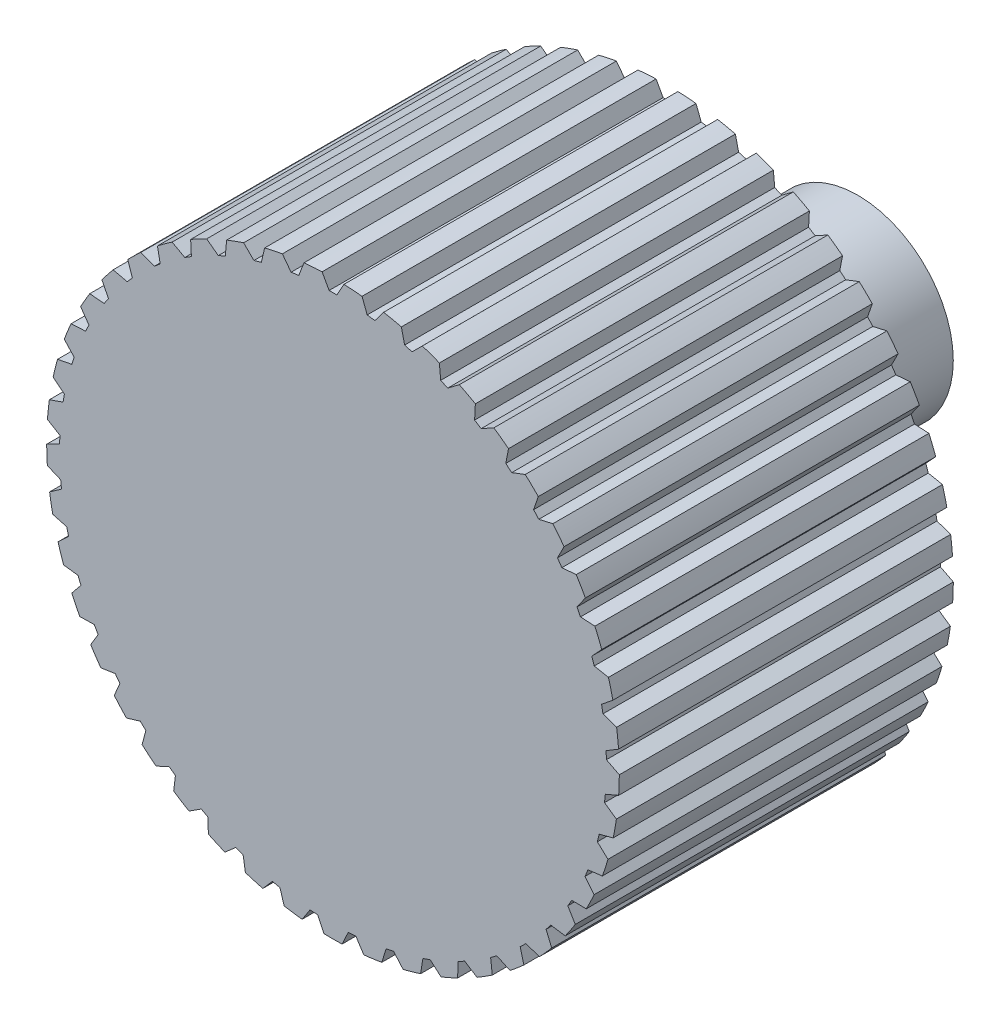
SolidWorks part; units mm, degrees
ref_plane "Plan de face" through (0, 0, 0) normal (0, 0, 1) x (1, 0, 0)
ref_plane "Plan de dessus" through (0, 0, 0) normal (0, 1, 0) x (1, 0, 0)
ref_plane "Plan de droite" through (0, 0, 0) normal (1, 0, 0) x (0, 0, -1)
sketch "Esquisse1" plane through (0, 0, 0) normal (0, 0, 1) x (1, 0, 0)
  line L0 (-0.1143, 2.9978) -> (-0.0406, 2.8652)
  line L1 (0.0406, 2.8652) -> (0.1143, 2.9978)
  line L2 (0, 2.8652) -> (0, 0) construction
  line L3 (-0.0406, 2.8652) -> (0.0406, 2.8652)
  line L4 (0.439, 2.8316) -> (0.5304, 2.9527)
  line L5 (0.3041, 2.9846) -> (0.3585, 2.8429)
  line L6 (0.3585, 2.8429) -> (0.439, 2.8316)
  line L7 (0.8288, 2.743) -> (0.9362, 2.8502)
  line L8 (0.7165, 2.9132) -> (0.7507, 2.7654)
  line L9 (0.7507, 2.7654) -> (0.8288, 2.743)
  line L10 (1.2025, 2.6009) -> (1.3237, 2.6922)
  line L11 (1.1149, 2.7851) -> (1.1283, 2.634)
  line L12 (1.1283, 2.634) -> (1.2025, 2.6009)
  line L13 (1.5527, 2.4083) -> (1.6855, 2.4817)
  line L14 (1.4917, 2.6029) -> (1.4839, 2.4513)
  line L15 (1.4839, 2.4513) -> (1.5527, 2.4083)
  line L16 (1.8728, 2.1687) -> (2.0145, 2.223)
  line L17 (1.8394, 2.3699) -> (1.8106, 2.2209)
  line L18 (1.8106, 2.2209) -> (1.8728, 2.1687)
  line L19 (2.1564, 1.887) -> (2.3043, 1.921)
  line L20 (2.1514, 2.0909) -> (2.1021, 1.9473)
  line L21 (2.1021, 1.9473) -> (2.1564, 1.887)
  line L22 (2.398, 1.5685) -> (2.5492, 1.5816)
  line L23 (2.4214, 1.7711) -> (2.3526, 1.6358)
  line L24 (2.3526, 1.6358) -> (2.398, 1.5685)
  line L25 (2.593, 1.2195) -> (2.7445, 1.2114)
  line L26 (2.6443, 1.4169) -> (2.5574, 1.2925)
  line L27 (2.5574, 1.2925) -> (2.593, 1.2195)
  line L28 (2.7375, 0.8468) -> (2.8864, 0.8177)
  line L29 (2.8158, 1.0351) -> (2.7124, 0.924)
  line L30 (2.7124, 0.924) -> (2.7375, 0.8468)
  line L31 (2.8287, 0.4575) -> (2.9721, 0.408)
  line L32 (2.9324, 0.6331) -> (2.8146, 0.5375)
  line L33 (2.8146, 0.5375) -> (2.8287, 0.4575)
  line L34 (2.8648, 0.0594) -> (3, -0.0096)
  line L35 (2.992, 0.2188) -> (2.862, 0.1406)
  line L36 (2.862, 0.1406) -> (2.8648, 0.0594)
  line L37 (2.8452, -0.3399) -> (2.9695, -0.427)
  line L38 (2.9933, -0.1997) -> (2.8537, -0.2591)
  line L39 (2.8537, -0.2591) -> (2.8452, -0.3399)
  line L40 (2.7702, -0.7325) -> (2.8811, -0.8361)
  line L41 (2.9364, -0.6144) -> (2.7899, -0.6537)
  line L42 (2.7899, -0.6537) -> (2.7702, -0.7325)
  line L43 (2.6413, -1.111) -> (2.7367, -1.229)
  line L44 (2.8223, -1.017) -> (2.6717, -1.0357)
  line L45 (2.6717, -1.0357) -> (2.6413, -1.111)
  line L46 (2.461, -1.4677) -> (2.5391, -1.5979)
  line L47 (2.6533, -1.3999) -> (2.5016, -1.3974)
  line L48 (2.5016, -1.3974) -> (2.461, -1.4677)
  line L49 (2.2328, -1.796) -> (2.292, -1.9357)
  line L50 (2.4327, -1.7556) -> (2.2828, -1.732)
  line L51 (2.2828, -1.732) -> (2.2328, -1.796)
  line L52 (1.9611, -2.0892) -> (2.0003, -2.2358)
  line L53 (2.1647, -2.0771) -> (2.0195, -2.0328)
  line L54 (2.0195, -2.0328) -> (1.9611, -2.0892)
  line L55 (1.6512, -2.3418) -> (1.6696, -2.4925)
  line L56 (1.8545, -2.3581) -> (1.7169, -2.2941)
  line L57 (1.7169, -2.2941) -> (1.6512, -2.3418)
  line L58 (1.3093, -2.5488) -> (1.3065, -2.7006)
  line L59 (1.5083, -2.5933) -> (1.381, -2.5107)
  line L60 (1.381, -2.5107) -> (1.3093, -2.5488)
  line L61 (0.9418, -2.7063) -> (0.9179, -2.8561)
  line L62 (1.1327, -2.7779) -> (1.0181, -2.6785)
  line L63 (1.0181, -2.6785) -> (0.9418, -2.7063)
  line L64 (0.556, -2.811) -> (0.5115, -2.9561)
  line L65 (0.7351, -2.9086) -> (0.6354, -2.7941)
  line L66 (0.6354, -2.7941) -> (0.556, -2.811)
  line L67 (0.1594, -2.861) -> (0.0951, -2.9985)
  line L68 (0.3231, -2.9825) -> (0.2404, -2.8553)
  line L69 (0.2404, -2.8553) -> (0.1594, -2.861)
  line L70 (-0.2404, -2.8553) -> (-0.3231, -2.9825)
  line L71 (-0.0951, -2.9985) -> (-0.1594, -2.861)
  line L72 (-0.1594, -2.861) -> (-0.2404, -2.8553)
  line L73 (-0.6354, -2.7941) -> (-0.7351, -2.9086)
  line L74 (-0.5115, -2.9561) -> (-0.556, -2.811)
  line L75 (-0.556, -2.811) -> (-0.6354, -2.7941)
  line L76 (-1.0181, -2.6785) -> (-1.1327, -2.7779)
  line L77 (-0.9179, -2.8561) -> (-0.9418, -2.7063)
  line L78 (-0.9418, -2.7063) -> (-1.0181, -2.6785)
  line L79 (-1.381, -2.5107) -> (-1.5083, -2.5933)
  line L80 (-1.3065, -2.7006) -> (-1.3093, -2.5488)
  line L81 (-1.3093, -2.5488) -> (-1.381, -2.5107)
  line L82 (-1.7169, -2.2941) -> (-1.8545, -2.3581)
  line L83 (-1.6696, -2.4925) -> (-1.6512, -2.3418)
  line L84 (-1.6512, -2.3418) -> (-1.7169, -2.2941)
  line L85 (-2.0195, -2.0328) -> (-2.1647, -2.0771)
  line L86 (-2.0003, -2.2358) -> (-1.9611, -2.0892)
  line L87 (-1.9611, -2.0892) -> (-2.0195, -2.0328)
  line L88 (-2.2828, -1.732) -> (-2.4327, -1.7556)
  line L89 (-2.292, -1.9357) -> (-2.2328, -1.796)
  line L90 (-2.2328, -1.796) -> (-2.2828, -1.732)
  line L91 (-2.5016, -1.3974) -> (-2.6533, -1.3999)
  line L92 (-2.5391, -1.5979) -> (-2.461, -1.4677)
  line L93 (-2.461, -1.4677) -> (-2.5016, -1.3974)
  line L94 (-2.6717, -1.0357) -> (-2.8223, -1.017)
  line L95 (-2.7367, -1.229) -> (-2.6413, -1.111)
  line L96 (-2.6413, -1.111) -> (-2.6717, -1.0357)
  line L97 (-2.7899, -0.6537) -> (-2.9364, -0.6144)
  line L98 (-2.8811, -0.8361) -> (-2.7702, -0.7325)
  line L99 (-2.7702, -0.7325) -> (-2.7899, -0.6537)
  line L100 (-2.8537, -0.2591) -> (-2.9933, -0.1997)
  line L101 (-2.9695, -0.427) -> (-2.8452, -0.3399)
  line L102 (-2.8452, -0.3399) -> (-2.8537, -0.2591)
  line L103 (-2.862, 0.1406) -> (-2.992, 0.2188)
  line L104 (-3, -0.0096) -> (-2.8648, 0.0594)
  line L105 (-2.8648, 0.0594) -> (-2.862, 0.1406)
  line L106 (-2.8146, 0.5375) -> (-2.9324, 0.6331)
  line L107 (-2.9721, 0.408) -> (-2.8287, 0.4575)
  line L108 (-2.8287, 0.4575) -> (-2.8146, 0.5375)
  line L109 (-2.7124, 0.924) -> (-2.8158, 1.0351)
  line L110 (-2.8864, 0.8177) -> (-2.7375, 0.8468)
  line L111 (-2.7375, 0.8468) -> (-2.7124, 0.924)
  line L112 (-2.5574, 1.2925) -> (-2.6443, 1.4169)
  line L113 (-2.7445, 1.2114) -> (-2.593, 1.2195)
  line L114 (-2.593, 1.2195) -> (-2.5574, 1.2925)
  line L115 (-2.3526, 1.6358) -> (-2.4214, 1.7711)
  line L116 (-2.5492, 1.5816) -> (-2.398, 1.5685)
  line L117 (-2.398, 1.5685) -> (-2.3526, 1.6358)
  line L118 (-2.1021, 1.9473) -> (-2.1514, 2.0909)
  line L119 (-2.3043, 1.921) -> (-2.1564, 1.887)
  line L120 (-2.1564, 1.887) -> (-2.1021, 1.9473)
  line L121 (-1.8106, 2.2209) -> (-1.8394, 2.3699)
  line L122 (-2.0145, 2.223) -> (-1.8728, 2.1687)
  line L123 (-1.8728, 2.1687) -> (-1.8106, 2.2209)
  line L124 (-1.4839, 2.4513) -> (-1.4917, 2.6029)
  line L125 (-1.6855, 2.4817) -> (-1.5527, 2.4083)
  line L126 (-1.5527, 2.4083) -> (-1.4839, 2.4513)
  line L127 (-1.1283, 2.634) -> (-1.1149, 2.7851)
  line L128 (-1.3237, 2.6922) -> (-1.2025, 2.6009)
  line L129 (-1.2025, 2.6009) -> (-1.1283, 2.634)
  line L130 (-0.7507, 2.7654) -> (-0.7165, 2.9132)
  line L131 (-0.9362, 2.8502) -> (-0.8288, 2.743)
  line L132 (-0.8288, 2.743) -> (-0.7507, 2.7654)
  line L133 (-0.3585, 2.8429) -> (-0.3041, 2.9846)
  line L134 (-0.5304, 2.9527) -> (-0.439, 2.8316)
  line L135 (-0.439, 2.8316) -> (-0.3585, 2.8429)
  arc A0 (-2.8811, -0.8361) -> (-2.8223, -1.017) centre (0, 0) ccw
  arc A1 (-2.7367, -1.229) -> (-2.6533, -1.3999) centre (0, 0) ccw
  arc A2 (-2.5391, -1.5979) -> (-2.4327, -1.7556) centre (0, 0) ccw
  arc A3 (-2.292, -1.9357) -> (-2.9364, -0.6144) centre (0, 0) ccw
  point P2 (0, 0)
  point P187 (0, 0)
  dimension "D1" = 6
  dimension "D2" = 45
extrude "Boss.-Extru.7" add sketch "Esquisse1" along normal blind 3.5 contours L101 A3 L97 L99 L98 A0 L94 L96 L95 A1 L91 L93 L92 A2 L88 L90 L89 L85 L87 L86 L82 L84 L83 L79 L81 L80 L76 L78 L77 L73 L75 L74 L70 L72 L71 L67 L69 L68 L64 L66 L65 L61
sketch "Esquisse2" plane through (0, 0, 0) normal (0, 0, -1) x (-1, 0, 0)
  circle A0 centre (0, 0) radius 1
extrude "Boss.-Extru.8" add sketch "Esquisse2" along normal blind 2
